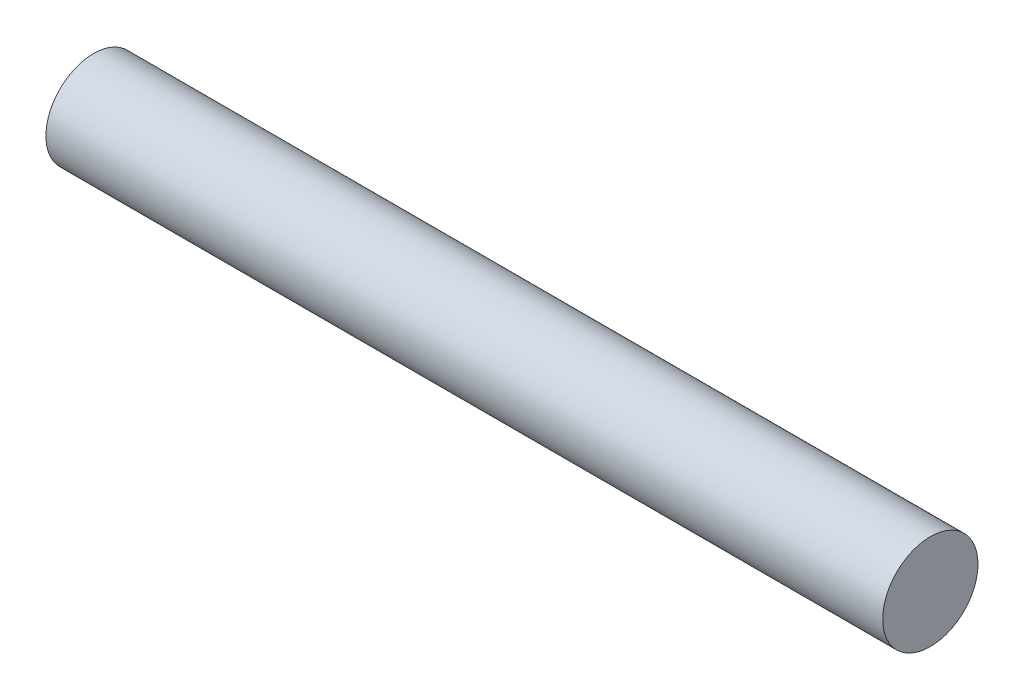
SolidWorks part; units mm, degrees
material "AISI 1020"
ref_plane "Front Plane" through (0, 0, 0) normal (0, 0, 1) x (1, 0, 0)
ref_plane "Top Plane" through (0, 0, 0) normal (0, 1, 0) x (1, 0, 0)
ref_plane "Right Plane" through (0, 0, 0) normal (1, 0, 0) x (0, 0, -1)
sketch "Sketch1" plane through (0, 0, 0) normal (1, 0, 0) x (0, 0, -1)
  circle A0 centre (0, 0) radius 5
  dimension "D1" = 10
extrude "Boss-Extrude1" add sketch "Sketch1" along normal blind 87.8
